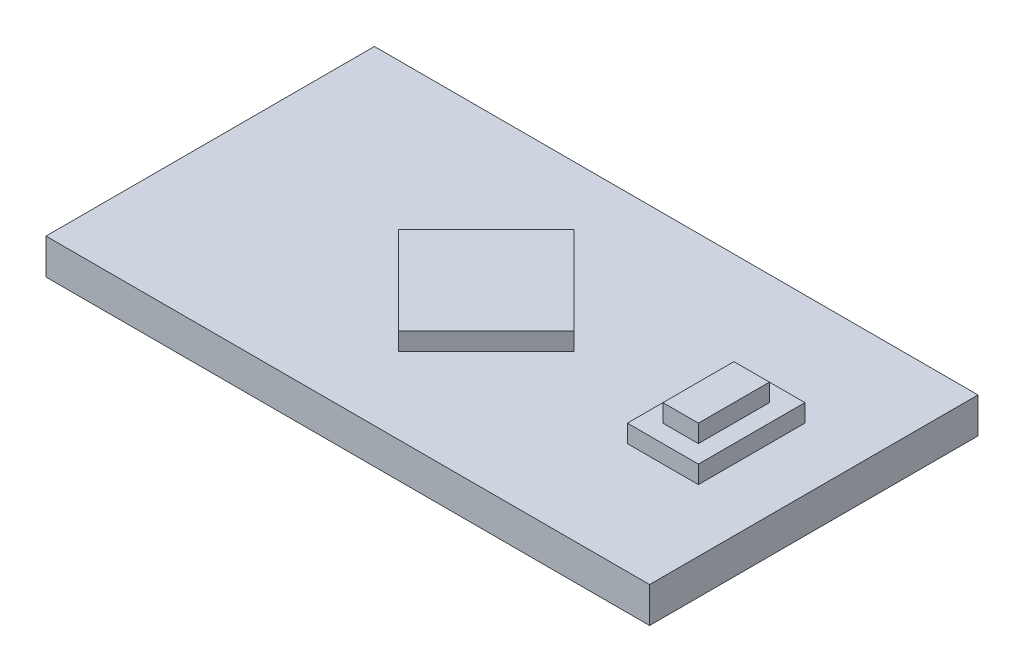
SolidWorks part; units mm, degrees
ref_plane "Front Plane" through (0, 0, 0) normal (0, 0, 1) x (1, 0, 0)
ref_plane "Top Plane" through (0, 0, 0) normal (0, 1, 0) x (1, 0, 0)
ref_plane "Right Plane" through (0, 0, 0) normal (1, 0, 0) x (0, 0, -1)
sketch "Sketch1" plane through (0, 0, 0) normal (0, 1, 0) x (1, 0, 0)
  line L1 (-17, -9.25) -> (17, -9.25)
  line L2 (-17, -9.25) -> (-17, 9.25)
  line L3 (-17, 9.25) -> (17, 9.25)
  line L4 (17, -9.25) -> (17, 9.25)
  point P4 (17, 0)
  point P6 (0, 9.25)
  dimension "D1" = 18.5
  dimension "D2" = 34
extrude "Boss-Extrude1" add sketch "Sketch1" along normal blind 2
sketch "Sketch2" plane through (0, 2, 0) normal (0, 1, 0) x (1, 0, 0)
  line L0 (17, -9.25) -> (17, 9.25) construction
  line L1 (13.5, 3) -> (9.5, 3)
  line L2 (13.5, 3) -> (13.5, -3)
  line L3 (13.5, -3) -> (9.5, -3)
  line L4 (9.5, 3) -> (9.5, -3)
  point P4 (9.5, 0)
  dimension "D1" = 3.5
  dimension "D2" = 4
  dimension "D3" = 6
extrude "Boss-Extrude2" add sketch "Sketch2" along normal blind 1
sketch "Sketch3" plane through (0, 3, 0) normal (0, 1, 0) x (1, 0, 0)
  line L0 (12.5, -2) -> (12.5, 2)
  line L1 (12.5, 2) -> (10.5, 2)
  line L2 (10.5, 2) -> (10.5, -2)
  line L3 (10.5, -2) -> (12.5, -2)
  line L4 (13.5, -3) -> (13.5, 3)
  line L5 (13.5, 3) -> (9.5, 3)
  line L6 (9.5, 3) -> (9.5, -3)
  line L7 (9.5, -3) -> (13.5, -3)
  line L8 (13.5, -3) -> (13.5, 3) construction
  line L9 (13.5, 3) -> (9.5, 3) construction
  line L10 (9.5, 3) -> (9.5, -3) construction
  line L11 (9.5, -3) -> (13.5, -3) construction
  dimension "D1" = 0
  dimension "D2" = 1
extrude "Boss-Extrude3" add sketch "Sketch3" along normal blind 1
sketch "Sketch4" plane through (0, 2, 0) normal (0, 1, 0) x (1, 0, 0)
  line L0 (3.5, 0) -> (-1.4497, 4.9497)
  line L1 (3.5, 0) -> (-1.4497, -4.9497)
  line L2 (-1.4497, 4.9497) -> (-6.3995, 0)
  line L3 (-1.4497, -4.9497) -> (-6.3995, 0)
  line L4 (17, -9.25) -> (17, 9.25) construction
  point P0 (0, 0)
  dimension "D1" = 7
  dimension "D2" = 13.5
extrude "Boss-Extrude4" add sketch "Sketch4" along normal blind 1
